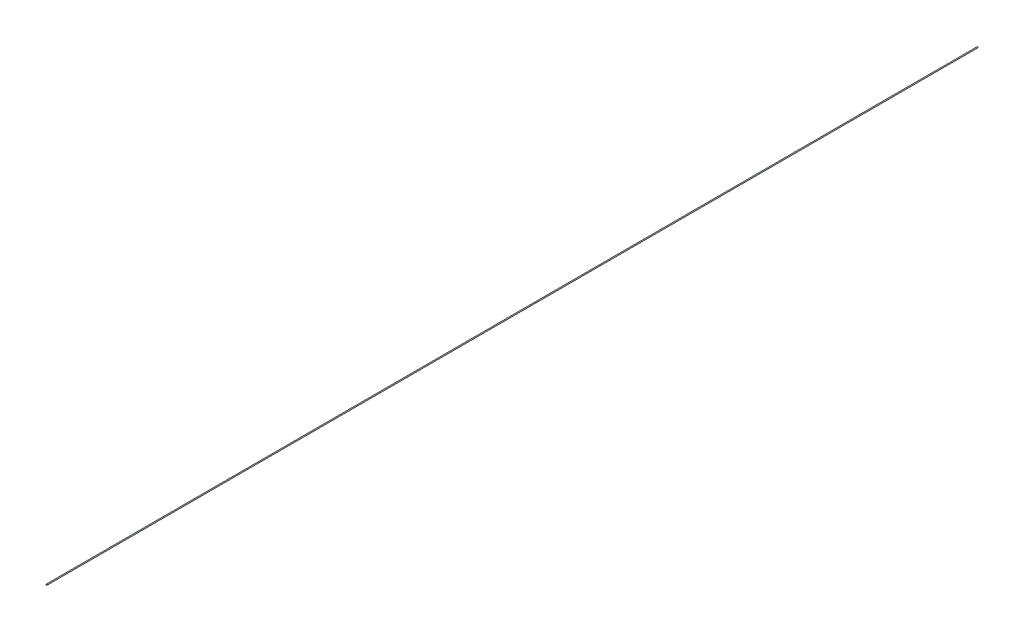
SolidWorks part; units mm, degrees
ref_plane "Front Plane" through (0, 0, 0) normal (0, 0, 1) x (1, 0, 0)
ref_plane "Top Plane" through (0, 0, 0) normal (0, 1, 0) x (1, 0, 0)
ref_plane "Right Plane" through (0, 0, 0) normal (1, 0, 0) x (0, 0, -1)
sketch "Sketch1" plane through (0, 0, 0) normal (0, 0, 1) x (1, 0, 0)
  circle A0 centre (0, 0) radius 4
  dimension "D1" = 8
extrude "Boss-Extrude1" add sketch "Sketch1" along normal blind 7620
fillet "Fillet1" radius 3 2 edges at (4, 0, 7620) (4, 0, 0)
